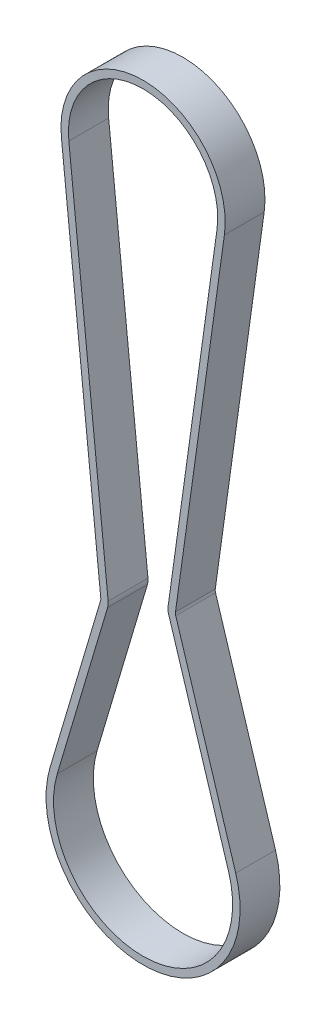
SolidWorks part; units mm, degrees
ref_plane "前视" through (0, 0, 0) normal (0, 0, 1) x (1, 0, 0)
ref_plane "上视" through (0, 0, 0) normal (0, 1, 0) x (1, 0, 0)
ref_plane "右视" through (0, 0, 0) normal (1, 0, 0) x (0, 0, -1)
sketch "草图1" plane through (0, 0, 0) normal (0, 0, 1) x (1, 0, 0)
  line L0 (0, 76.304) -> (0, -41.696) construction
  line L1 (0, -1.696) -> (-10, -1.696) construction
  line L2 (0, 3.304) -> (8, 3.304) construction
  line L3 (-14.9198, 74.7552) -> (-7.016, -1.3863)
  line L4 (-7.1248, -2.5522) -> (-17.2514, -36.5589)
  line L5 (5.1353, 2.4133) -> (17.1883, -36.3517)
  line L6 (14.8564, 74.2335) -> (5.0287, 3.7181)
  line L7 (-16.4118, 74.6004) -> (-8.508, -1.5411)
  line L8 (-8.5624, -2.1241) -> (-18.689, -36.1308)
  line L9 (6.5676, 2.8586) -> (18.6207, -35.9064)
  line L10 (16.3421, 74.0264) -> (6.5144, 3.511)
  arc A0 (14.8564, 74.2335) -> (-14.9198, 74.7552) centre (0, 76.304) ccw
  arc A1 (-17.2514, -36.5589) -> (17.1883, -36.3517) centre (0, -41.696) ccw
  arc A2 (-7.1248, -2.5522) -> (-7.016, -1.3863) centre (-10, -1.696) ccw
  arc A3 (5.0287, 3.7181) -> (5.1353, 2.4133) centre (8, 3.304) ccw
  arc A4 (-8.5624, -2.1241) -> (-8.508, -1.5411) centre (-10, -1.696) ccw
  arc A5 (-18.689, -36.1308) -> (18.6207, -35.9064) centre (0, -41.696) ccw
  arc A6 (6.5144, 3.511) -> (6.5676, 2.8586) centre (8, 3.304) ccw
  arc A7 (16.3421, 74.0264) -> (-16.4118, 74.6004) centre (0, 76.304) ccw
  dimension "D1" = 30
  dimension "D2" = 36
  dimension "D8" = 6
  dimension "D9" = 6
  dimension "D3" = 118
  dimension "D4" = 40
  dimension "D5" = 5
  dimension "D6" = 10
  dimension "D7" = 8
  dimension "D10" = 1.5
extrude "凸台-拉伸1" add sketch "草图1" along normal blind 8 contours L3 A2 L4 A1 L5 A3 L6 A0 | A7 L7 A4 L8 A5 L9 A6 L10
